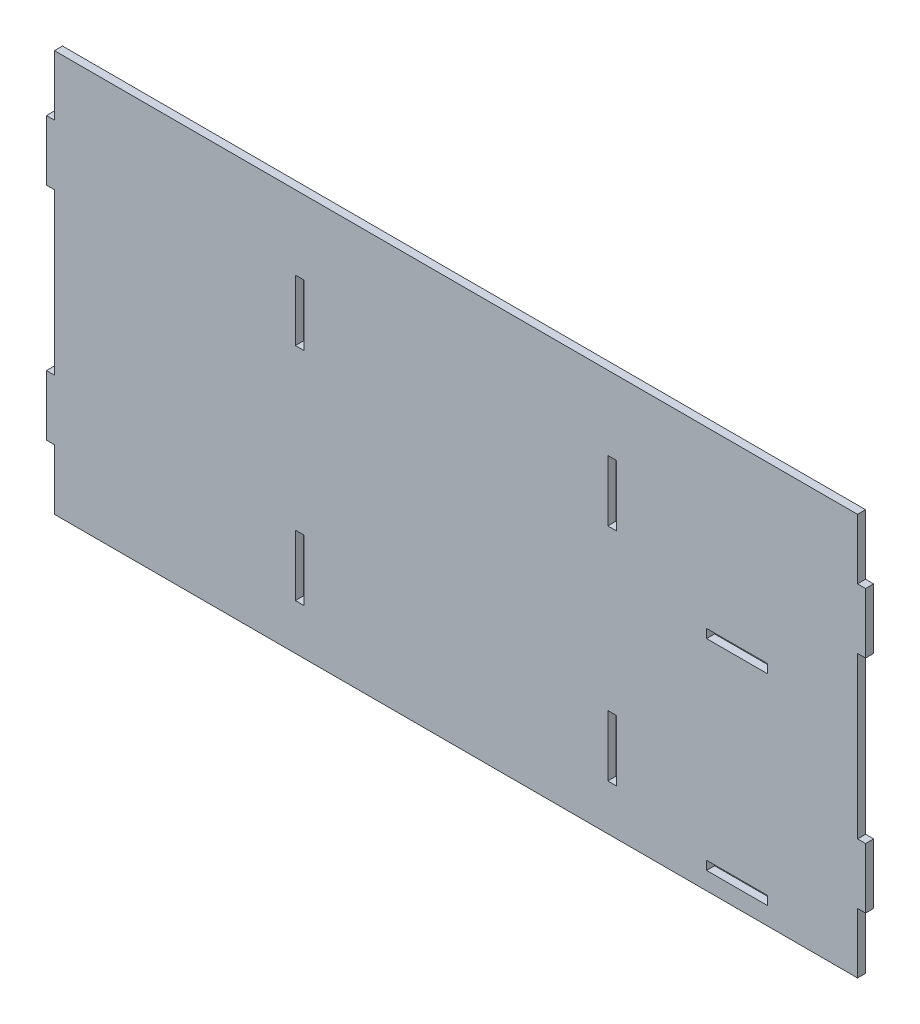
SolidWorks part; units mm, degrees
ref_plane "Спереди" through (0, 0, 0) normal (0, 0, 1) x (1, 0, 0)
ref_plane "Сверху" through (0, 0, 0) normal (0, 1, 0) x (1, 0, 0)
ref_plane "Справа" through (0, 0, 0) normal (1, 0, 0) x (0, 0, -1)
sketch "Эскиз1" plane through (0, 0, 0) normal (0, 0, 1) x (1, 0, 0)
  line L0 (0, 0) -> (-200, 0) construction
  line L1 (-200, 100) -> (200, 100)
  line L2 (-200, 100) -> (-200, -100)
  line L3 (-200, -100) -> (200, -100)
  line L4 (200, 100) -> (200, -100)
  line L5 (-200, 100) -> (200, -100) construction
  line L6 (-200, -100) -> (200, 100) construction
  line L7 (-200, -40) -> (-204, -40)
  line L8 (-200, -40) -> (-200, -70)
  line L9 (-200, -70) -> (-204, -70)
  line L10 (-204, -40) -> (-204, -70)
  line L11 (0, 0) -> (0, -100) construction
  line L12 (-200, 70) -> (-204, 70)
  line L13 (-204, 40) -> (-204, 70)
  line L14 (-200, 40) -> (-204, 40)
  line L15 (-200, 40) -> (-200, 70)
  line L16 (200, -70) -> (204, -70)
  line L17 (204, -40) -> (204, -70)
  line L18 (200, -40) -> (204, -40)
  line L19 (200, -40) -> (200, -70)
  line L20 (200, 40) -> (200, 70)
  line L21 (200, 40) -> (204, 40)
  line L22 (204, 40) -> (204, 70)
  line L23 (200, 70) -> (204, 70)
  line L24 (75.6, -46.8) -> (75.6, 32.8) construction
  line L25 (75.6, -77.2) -> (80, -77.2)
  line L26 (75.6, -77.2) -> (75.6, -46.8)
  line L27 (75.6, -46.8) -> (80, -46.8)
  line L28 (80, -77.2) -> (80, -46.8)
  line L29 (75.6, 32.8) -> (80, 32.8)
  line L30 (75.6, 32.8) -> (75.6, 63.2)
  line L31 (75.6, 63.2) -> (80, 63.2)
  line L32 (80, 32.8) -> (80, 63.2)
  line L33 (80, -46.8) -> (80, 32.8) construction
  line L34 (75.6, 48) -> (80, 48) construction
  line L35 (75.6, -62) -> (80, -62) construction
  line L36 (-80, 32.8) -> (-80, -46.8) construction
  line L37 (-80, -77.2) -> (-75.6, -77.2)
  line L38 (-80, -77.2) -> (-80, -46.8)
  line L39 (-80, -46.8) -> (-75.6, -46.8)
  line L40 (-75.6, -77.2) -> (-75.6, -46.8)
  line L41 (-80, 32.8) -> (-75.6, 32.8)
  line L42 (-80, 32.8) -> (-80, 63.2)
  line L43 (-80, 63.2) -> (-75.6, 63.2)
  line L44 (-75.6, 32.8) -> (-75.6, 63.2)
  line L45 (-75.6, -46.8) -> (-75.6, 32.8) construction
  line L46 (-75.6, -77.2) -> (75.6, -77.2) construction
  line L47 (-80, -62) -> (-75.6, -62) construction
  line L48 (-80, 48) -> (-75.6, 48) construction
  line L49 (140, -91.2) -> (140, -86.8) construction
  line L50 (124.8, -86.8) -> (155.2, -86.8)
  line L51 (124.8, -86.8) -> (124.8, -91.2)
  line L52 (124.8, -91.2) -> (155.2, -91.2)
  line L53 (155.2, -86.8) -> (155.2, -91.2)
  line L54 (124.8, -89) -> (155.2, -89) construction
  line L55 (124.8, 13.2) -> (124.8, 8.8)
  line L56 (124.8, 13.2) -> (155.2, 13.2)
  line L57 (155.2, 13.2) -> (155.2, 8.8)
  line L58 (124.8, 8.8) -> (155.2, 8.8)
  line L59 (124.8, -86.8) -> (124.8, 13.2) construction
  point P0 (0, 0)
  dimension "D1" = 400
  dimension "D2" = 200
  dimension "D3" = 4
  dimension "D4" = 30
  dimension "D5" = 40
  dimension "D6" = 120
  dimension "D7" = 30.4
  dimension "D8" = 30.4
  dimension "D9" = 4.4
  dimension "D10" = 110
  dimension "D11" = 38
  dimension "D12" = 30.4
  dimension "D13" = 30.4
  dimension "D14" = 4.4
  dimension "D15" = 120
  dimension "D16" = 110
  dimension "D17" = 11
  dimension "D18" = 60
  dimension "D19" = 30.4
  dimension "D20" = 4.4
  dimension "D21" = 2
  dimension "D22" = 100
extrude "Бобышка-Вытянуть1" add sketch "Эскиз1" along normal blind 4 contours L4 L1 L2 L3 | L14 L2 L12 L13 | L7 L10 L9 L2 | L23 L4 L21 L22 | L18 L4 L16 L17
